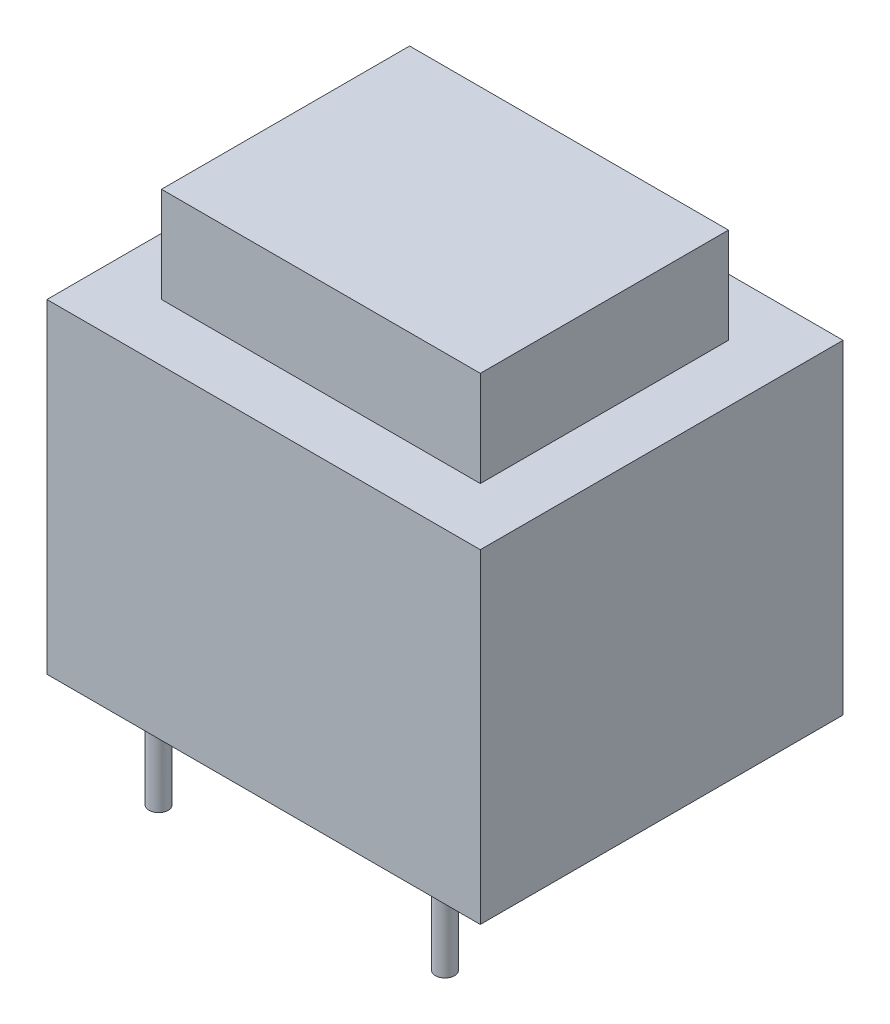
SolidWorks part; units mm, degrees
ref_plane "Front Plane" through (0, 0, 0) normal (0, 0, 1) x (1, 0, 0)
ref_plane "Top Plane" through (0, 0, 0) normal (0, 1, 0) x (1, 0, 0)
ref_plane "Right Plane" through (0, 0, 0) normal (1, 0, 0) x (0, 0, -1)
sketch "Sketch2" plane through (0, 0, 0) normal (0, 0, 1) x (1, 0, 0)
  line L1 (0, 0) -> (22.7, 0)
  line L2 (0, 0) -> (0, -22)
  line L3 (0, -22) -> (22.7, -22)
  line L4 (22.7, 0) -> (22.7, -22)
  dimension "D1" = 22.7
  dimension "D2" = 22
extrude "Boss-Extrude1" add sketch "Sketch2" along normal blind 19
sketch "Sketch3" plane through (0, -22, 0) normal (0, -1, 0) x (1, 0, 0)
  line L0 (18.85, 17) -> (3.85, 17) construction
  line L9 (13.85, 2) -> (8.85, 2) construction
  line L10 (11.35, 2) -> (11.35, 17) construction
  line L11 (22.7, 19) -> (22.7, 0) construction
  line L12 (0, 19) -> (0, 0) construction
  line L19 (14.77, 9.5) -> (7.7629, 9.5) construction
  line L20 (0, 0) -> (22.7, 0) construction
  line L21 (0, 19) -> (22.7, 19) construction
  circle A0 centre (18.85, 17) radius 0.5
  circle A1 centre (3.85, 17) radius 0.5
  circle A2 centre (8.85, 2) radius 0.5
  circle A3 centre (13.85, 2) radius 0.5
  point P16 (11.35, 9.5)
  dimension "D4" = 1
  dimension "D5" = 1
  dimension "D6" = 1
  dimension "D7" = 1
  dimension "D1" = 15
  dimension "D2" = 15
  dimension "D3" = 5
extrude "Boss-Extrude2" add sketch "Sketch3" along normal blind 5
sketch "Sketch5" plane through (0, 0, 0) normal (0, 1, 0) x (1, 0, 0)
  line L1 (0, 0) -> (22.7, 0)
  line L2 (0, 0) -> (0, -19)
  line L3 (0, -19) -> (22.7, -19)
  line L4 (22.7, 0) -> (22.7, -19)
  line L5 (3, -3.0036) -> (19.7, -3.0036)
  line L6 (3, -3.0036) -> (3, -16)
  line L7 (3, -16) -> (19.7, -16)
  line L8 (19.7, -3.0036) -> (19.7, -16)
  dimension "D1" = 3.0036
  dimension "D2" = 3
  dimension "D3" = 3
  dimension "D4" = 3
extrude "Cut-Extrude1" cut sketch "Sketch5" against normal blind 5
